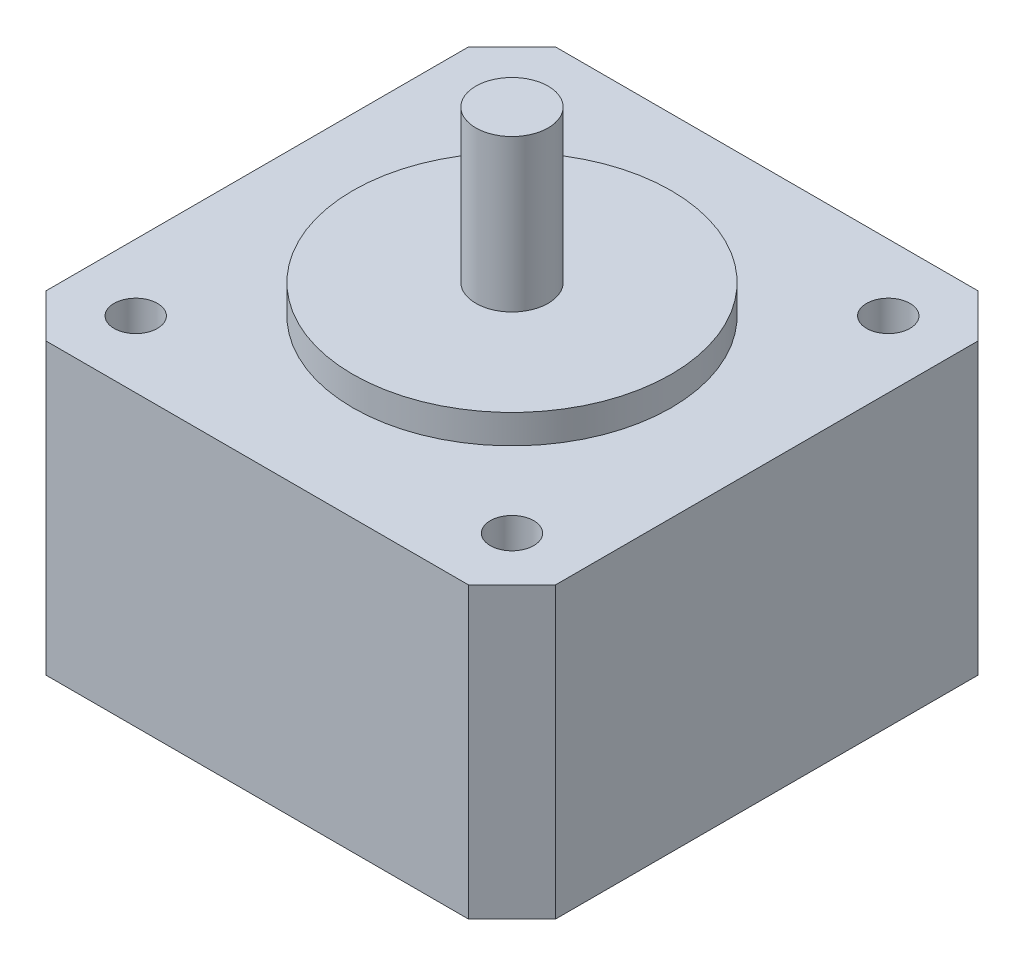
SolidWorks part; units mm, degrees
ref_plane "Front Plane" through (0, 0, 0) normal (0, 0, 1) x (1, 0, 0)
ref_plane "Top Plane" through (0, 0, 0) normal (0, 1, 0) x (1, 0, 0)
ref_plane "Right Plane" through (0, 0, 0) normal (1, 0, 0) x (0, 0, -1)
sketch "Sketch1" plane through (0, 0, 0) normal (0, 1, 0) x (1, 0, 0)
  line L1 (-17.6, -17.6) -> (17.6, -17.6)
  line L2 (-17.6, -17.6) -> (-17.6, 17.6)
  line L3 (-17.6, 17.6) -> (17.6, 17.6)
  line L4 (17.6, -17.6) -> (17.6, 17.6)
  line L5 (-17.6, -17.6) -> (17.6, 17.6) construction
  line L6 (-17.6, 17.6) -> (17.6, -17.6) construction
  point P0 (0, 0)
  dimension "D1" = 35.2
  dimension "D2" = 35.2
extrude "Boss-Extrude1" add sketch "Sketch1" along normal blind 20
sketch "Sketch2" plane through (0, 20, 0) normal (0, 1, 0) x (1, 0, 0)
  circle A0 centre (0, 0) radius 11
  dimension "D1" = 22
extrude "Boss-Extrude2" add sketch "Sketch2" along normal blind 2
sketch "Sketch3" plane through (0, 22, 0) normal (0, 1, 0) x (1, 0, 0)
  circle A0 centre (0, 0) radius 2.5
  dimension "D1" = 5
extrude "Boss-Extrude3" add sketch "Sketch3" along normal blind 10.5
sketch "Sketch4" plane through (0, 20, 0) normal (0, 1, 0) x (1, 0, 0)
  circle A0 centre (-13, 13) radius 1.5
  circle A1 centre (0, 0) radius 2.5 construction
  circle A2 centre (0, 0) radius 2.5 construction
  circle A3 centre (13, 13) radius 1.5
  circle A4 centre (13, -13) radius 1.5
  circle A5 centre (-13, -13) radius 1.5
  point P15 (0, 0)
  dimension "D1" = 13
  dimension "D2" = 13
  dimension "D3" = 3
  dimension "D4" = 4
extrude "Cut-Extrude1" cut sketch "Sketch4" against normal blind 4.5
chamfer "Chamfer1" distance 3 angle 45 4 edges at (-17.6, 10, 17.6) (-17.6, 10, -17.6) (17.6, 10, -17.6) (17.6, 10, 17.6)
